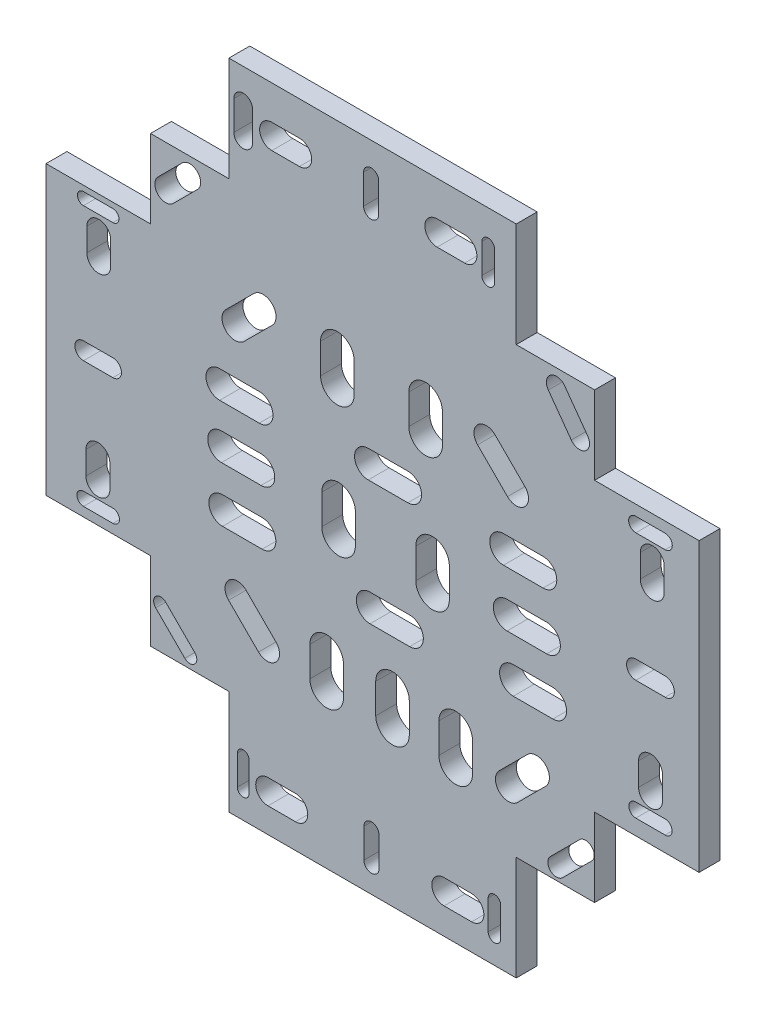
SolidWorks part; units mm, degrees
ref_plane "Front Plane" through (0, 0, 0) normal (0, 0, 1) x (1, 0, 0)
ref_plane "Top Plane" through (0, 0, 0) normal (0, 1, 0) x (1, 0, 0)
ref_plane "Right Plane" through (0, 0, 0) normal (1, 0, 0) x (0, 0, -1)
sketch "Sketch2" plane through (0, 0, 0) normal (0, 0, 1) x (1, 0, 0)
  line L0 (0, 0) -> (54.9967, 0)
  line L1 (54.9967, 0) -> (54.9967, 20.0012)
  line L2 (0, 0) -> (0, 20.0012)
  line L3 (0, 20.0012) -> (-15.0042, 20.0012)
  line L4 (-15.0042, 20.0012) -> (-15.0042, 34.9972)
  line L5 (-15.0042, 34.9972) -> (-35.003, 34.9972)
  line L6 (-35.003, 34.9972) -> (-35.003, 89.9966)
  line L7 (-35.003, 89.9966) -> (-15.0042, 89.9966)
  line L8 (-15.0042, 89.9966) -> (-15.0042, 104.9933)
  line L9 (-15.0042, 104.9933) -> (0, 104.9933)
  line L10 (0, 104.9933) -> (0, 124.9917)
  line L11 (0, 124.9917) -> (54.9967, 124.9917)
  line L12 (54.9967, 124.9917) -> (54.9967, 104.9933)
  line L13 (54.9967, 104.9933) -> (69.9972, 104.9933)
  line L14 (69.9972, 104.9933) -> (69.9972, 89.9966)
  line L15 (69.9972, 89.9966) -> (89.9963, 89.9966)
  line L16 (89.9963, 89.9966) -> (89.9963, 34.9972)
  line L17 (89.9963, 34.9972) -> (69.9972, 34.9972)
  line L18 (69.9972, 34.9972) -> (69.9972, 20.0012)
  line L19 (69.9972, 20.0012) -> (54.9967, 20.0012)
  line L20 (-27.8347, 38.0198) -> (-22.2091, 38.0198) construction
  line L21 (-27.8347, 39.2807) -> (-22.2091, 39.2807)
  line L22 (-27.8347, 36.7588) -> (-22.2091, 36.7588)
  line L23 (-27.8347, 87.778) -> (-22.2091, 87.778) construction
  line L24 (-27.8347, 88.9419) -> (-22.2091, 88.9419)
  line L25 (-27.8347, 86.6141) -> (-22.2091, 86.6141)
  line L26 (-27.8347, 62.5594) -> (-22.2091, 62.5594) construction
  line L27 (-27.8347, 64.2083) -> (-22.2091, 64.2083)
  line L28 (-27.8347, 60.9105) -> (-22.2091, 60.9105)
  line L29 (77.8808, 62.5594) -> (83.4988, 62.5594) construction
  line L30 (77.8808, 64.3223) -> (83.4988, 64.3223)
  line L31 (77.8808, 60.7965) -> (83.4988, 60.7965)
  line L32 (77.8808, 39.2807) -> (83.4988, 39.2807) construction
  line L33 (77.8808, 40.6133) -> (83.4988, 40.6133)
  line L34 (77.8808, 37.9481) -> (83.4988, 37.9481)
  line L35 (77.8808, 86.6141) -> (83.4988, 86.6141) construction
  line L36 (77.8808, 87.9828) -> (83.4988, 87.9828)
  line L37 (77.8808, 85.2454) -> (83.4988, 85.2454)
  line L38 (27.292, 4.9628) -> (27.292, 10.5841) construction
  line L39 (25.8409, 4.9628) -> (25.8409, 10.5841)
  line L40 (28.7431, 4.9628) -> (28.7431, 10.5841)
  line L41 (2.7367, 4.9628) -> (2.7367, 10.5841) construction
  line L42 (1.6165, 4.9628) -> (1.6165, 10.5841)
  line L43 (3.857, 4.9628) -> (3.857, 10.5841)
  line L44 (50.8285, 4.9628) -> (50.8285, 10.5841) construction
  line L45 (49.6282, 4.9628) -> (49.6282, 10.5841)
  line L46 (52.0288, 4.9628) -> (52.0288, 10.5841)
  line L47 (27.2281, 113.3425) -> (27.2281, 118.9638) construction
  line L50 (49.6282, 113.1494) -> (49.6282, 118.7625) construction
  line L51 (48.4049, 113.1494) -> (48.4049, 118.7625)
  line L52 (50.8515, 113.1494) -> (50.8515, 118.7625)
  line L53 (2.7367, 113.1494) -> (2.7367, 118.7625) construction
  line L54 (0.9482, 113.1494) -> (0.9482, 118.7625)
  line L55 (4.5253, 113.1494) -> (4.5253, 118.7625)
  line L56 (-13.0567, 27.8034) -> (-7.4882, 22.2349) construction
  line L57 (-12.1042, 28.7559) -> (-6.5356, 23.1874)
  line L58 (-14.0092, 26.8509) -> (-8.4407, 21.2823)
  line L59 (62.7052, 22.2349) -> (68.2737, 27.8034) construction
  line L60 (61.5328, 23.4072) -> (67.1014, 28.9758)
  line L61 (63.8775, 21.0625) -> (69.4461, 26.6311)
  line L62 (-12.1042, 97.0442) -> (-7.4882, 101.6603) construction
  line L63 (-13.5693, 98.5093) -> (-8.9533, 103.1254)
  line L64 (-10.6391, 95.5791) -> (-6.023, 100.1952)
  line L65 (62.7052, 101.6603) -> (67.1014, 95.5791) construction
  line L66 (64.2684, 102.7904) -> (68.6647, 96.7092)
  line L67 (61.1419, 100.5302) -> (65.5381, 94.449)
  line L68 (1.6165, 36.7588) -> (7.3377, 31.0376) construction
  line L69 (3.2847, 38.4271) -> (9.0059, 32.7059)
  line L70 (-0.0517, 35.0906) -> (5.6695, 29.3694)
  line L71 (58.873, 36.3537) -> (53.5044, 30.9851) construction
  line L72 (60.6273, 34.5995) -> (55.2587, 29.2309)
  line L73 (57.1187, 38.108) -> (51.7502, 32.7394)
  line L74 (6.5376, 86.6118) -> (1.169, 81.2432) construction
  line L75 (8.2918, 84.8575) -> (2.9233, 79.4889)
  line L76 (4.7833, 88.366) -> (-0.5853, 82.9975)
  line L77 (49.2661, 86.3508) -> (54.9873, 80.6296) construction
  line L78 (50.9344, 88.0191) -> (56.6556, 82.2979)
  line L79 (47.5979, 84.6826) -> (53.3191, 78.9614)
  line L80 (37.652, 81.1405) -> (37.652, 86.8617) construction
  line L81 (34.439, 81.1405) -> (34.439, 86.8617)
  line L82 (40.865, 81.1405) -> (40.865, 86.8617)
  line L83 (31.3153, 30.0156) -> (31.3153, 35.7368) construction
  line L84 (28.1023, 30.0156) -> (28.1023, 35.7368)
  line L85 (34.5283, 30.0156) -> (34.5283, 35.7368)
  line L86 (-1.2121, 49.3864) -> (6.3653, 49.3864) construction
  line L87 (-1.2121, 52.0097) -> (6.3653, 52.0097)
  line L88 (-1.2121, 46.7631) -> (6.3653, 46.7631)
  line L89 (-1.7652, 70.0017) -> (5.8123, 70.0017) construction
  line L90 (-1.7652, 72.625) -> (5.8123, 72.625)
  line L91 (-1.7652, 67.3784) -> (5.8123, 67.3784)
  line L92 (54.4341, 49.0547) -> (62.0115, 49.0547) construction
  line L93 (54.4341, 51.678) -> (62.0115, 51.678)
  line L94 (54.4341, 46.4314) -> (62.0115, 46.4314)
  line L95 (52.5607, 69.8314) -> (60.1382, 69.8314) construction
  line L96 (52.5607, 72.4547) -> (60.1382, 72.4547)
  line L97 (52.5607, 67.2081) -> (60.1382, 67.2081)
  line L98 (20.7566, 81.1058) -> (20.7566, 86.8269) construction
  line L99 (17.5436, 81.1058) -> (17.5436, 86.8269)
  line L100 (23.9696, 81.1058) -> (23.9696, 86.8269)
  line L101 (-1.4246, 59.8524) -> (6.1529, 59.8524) construction
  line L102 (-1.4246, 62.4757) -> (6.1529, 62.4757)
  line L103 (-1.4246, 57.2292) -> (6.1529, 57.2292)
  line L104 (53.2419, 59.2728) -> (60.8194, 59.2728) construction
  line L105 (53.2419, 61.896) -> (60.8194, 61.896)
  line L106 (53.2419, 56.6495) -> (60.8194, 56.6495)
  line L107 (18.713, 29.8453) -> (18.713, 35.5665) construction
  line L108 (15.5, 29.8453) -> (15.5, 35.5665)
  line L109 (21.926, 29.8453) -> (21.926, 35.5665)
  line L110 (43.4066, 29.5047) -> (43.4066, 35.2259) construction
  line L111 (40.1936, 29.5047) -> (40.1936, 35.2259)
  line L112 (46.6196, 29.5047) -> (46.6196, 35.2259)
  line L113 (20.9936, 56.2141) -> (20.9936, 61.9353) construction
  line L114 (17.7806, 56.2141) -> (17.7806, 61.9353)
  line L115 (24.2066, 56.2141) -> (24.2066, 61.9353)
  line L116 (38.9788, 56.2419) -> (38.9788, 61.9631) construction
  line L117 (35.7658, 56.2419) -> (35.7658, 61.9631)
  line L118 (42.1918, 56.2419) -> (42.1918, 61.9631)
  line L119 (27.0157, 47.3517) -> (34.5931, 47.3517) construction
  line L120 (27.0157, 49.975) -> (34.5931, 49.975)
  line L121 (27.0157, 44.7284) -> (34.5931, 44.7284)
  line L122 (26.6751, 71.0235) -> (34.2525, 71.0235) construction
  line L123 (26.6751, 73.6468) -> (34.2525, 73.6468)
  line L124 (26.6751, 68.4002) -> (34.2525, 68.4002)
  line L125 (25.777, 113.3425) -> (25.777, 118.9638)
  line L126 (28.6792, 113.3425) -> (28.6792, 118.9638)
  arc A0 (-27.8347, 39.2807) -> (-27.8347, 36.7588) centre (-27.8347, 38.0198) ccw
  arc A1 (-22.2091, 36.7588) -> (-22.2091, 39.2807) centre (-22.2091, 38.0198) ccw
  arc A2 (-27.8347, 88.9419) -> (-27.8347, 86.6141) centre (-27.8347, 87.778) ccw
  arc A3 (-22.2091, 86.6141) -> (-22.2091, 88.9419) centre (-22.2091, 87.778) ccw
  arc A4 (-27.8347, 64.2083) -> (-27.8347, 60.9105) centre (-27.8347, 62.5594) ccw
  arc A5 (-22.2091, 60.9105) -> (-22.2091, 64.2083) centre (-22.2091, 62.5594) ccw
  arc A6 (77.8808, 64.3223) -> (77.8808, 60.7965) centre (77.8808, 62.5594) ccw
  arc A7 (83.4988, 60.7965) -> (83.4988, 64.3223) centre (83.4988, 62.5594) ccw
  arc A8 (77.8808, 40.6133) -> (77.8808, 37.9481) centre (77.8808, 39.2807) ccw
  arc A9 (83.4988, 37.9481) -> (83.4988, 40.6133) centre (83.4988, 39.2807) ccw
  arc A10 (77.8808, 87.9828) -> (77.8808, 85.2454) centre (77.8808, 86.6141) ccw
  arc A11 (83.4988, 85.2454) -> (83.4988, 87.9828) centre (83.4988, 86.6141) ccw
  arc A12 (25.8409, 4.9628) -> (28.7431, 4.9628) centre (27.292, 4.9628) ccw
  arc A13 (28.7431, 10.5841) -> (25.8409, 10.5841) centre (27.292, 10.5841) ccw
  arc A14 (1.6165, 4.9628) -> (3.857, 4.9628) centre (2.7367, 4.9628) ccw
  arc A15 (3.857, 10.5841) -> (1.6165, 10.5841) centre (2.7367, 10.5841) ccw
  arc A16 (49.6282, 4.9628) -> (52.0288, 4.9628) centre (50.8285, 4.9628) ccw
  arc A17 (52.0288, 10.5841) -> (49.6282, 10.5841) centre (50.8285, 10.5841) ccw
  arc A20 (48.4049, 113.1494) -> (50.8515, 113.1494) centre (49.6282, 113.1494) ccw
  arc A21 (50.8515, 118.7625) -> (48.4049, 118.7625) centre (49.6282, 118.7625) ccw
  arc A22 (0.9482, 113.1494) -> (4.5253, 113.1494) centre (2.7367, 113.1494) ccw
  arc A23 (4.5253, 118.7625) -> (0.9482, 118.7625) centre (2.7367, 118.7625) ccw
  arc A24 (-12.1042, 28.7559) -> (-14.0092, 26.8509) centre (-13.0567, 27.8034) ccw
  arc A25 (-8.4407, 21.2823) -> (-6.5356, 23.1874) centre (-7.4882, 22.2349) ccw
  arc A26 (61.5328, 23.4072) -> (63.8775, 21.0625) centre (62.7052, 22.2349) ccw
  arc A27 (69.4461, 26.6311) -> (67.1014, 28.9758) centre (68.2737, 27.8034) ccw
  arc A28 (-13.5693, 98.5093) -> (-10.6391, 95.5791) centre (-12.1042, 97.0442) ccw
  arc A29 (-6.023, 100.1952) -> (-8.9533, 103.1254) centre (-7.4882, 101.6603) ccw
  arc A30 (64.2684, 102.7904) -> (61.1419, 100.5302) centre (62.7052, 101.6603) ccw
  arc A31 (65.5381, 94.449) -> (68.6647, 96.7092) centre (67.1014, 95.5791) ccw
  arc A32 (3.2847, 38.4271) -> (-0.0517, 35.0906) centre (1.6165, 36.7588) ccw
  arc A33 (5.6695, 29.3694) -> (9.0059, 32.7059) centre (7.3377, 31.0376) ccw
  arc A34 (60.6273, 34.5995) -> (57.1187, 38.108) centre (58.873, 36.3537) ccw
  arc A35 (51.7502, 32.7394) -> (55.2587, 29.2309) centre (53.5044, 30.9851) ccw
  arc A36 (8.2918, 84.8575) -> (4.7833, 88.366) centre (6.5376, 86.6118) ccw
  arc A37 (-0.5853, 82.9975) -> (2.9233, 79.4889) centre (1.169, 81.2432) ccw
  arc A38 (50.9344, 88.0191) -> (47.5979, 84.6826) centre (49.2661, 86.3508) ccw
  arc A39 (53.3191, 78.9614) -> (56.6556, 82.2979) centre (54.9873, 80.6296) ccw
  arc A40 (34.439, 81.1405) -> (40.865, 81.1405) centre (37.652, 81.1405) ccw
  arc A41 (40.865, 86.8617) -> (34.439, 86.8617) centre (37.652, 86.8617) ccw
  arc A42 (28.1023, 30.0156) -> (34.5283, 30.0156) centre (31.3153, 30.0156) ccw
  arc A43 (34.5283, 35.7368) -> (28.1023, 35.7368) centre (31.3153, 35.7368) ccw
  arc A44 (-1.2121, 52.0097) -> (-1.2121, 46.7631) centre (-1.2121, 49.3864) ccw
  arc A45 (6.3653, 46.7631) -> (6.3653, 52.0097) centre (6.3653, 49.3864) ccw
  arc A46 (-1.7652, 72.625) -> (-1.7652, 67.3784) centre (-1.7652, 70.0017) ccw
  arc A47 (5.8123, 67.3784) -> (5.8123, 72.625) centre (5.8123, 70.0017) ccw
  arc A48 (54.4341, 51.678) -> (54.4341, 46.4314) centre (54.4341, 49.0547) ccw
  arc A49 (62.0115, 46.4314) -> (62.0115, 51.678) centre (62.0115, 49.0547) ccw
  arc A50 (52.5607, 72.4547) -> (52.5607, 67.2081) centre (52.5607, 69.8314) ccw
  arc A51 (60.1382, 67.2081) -> (60.1382, 72.4547) centre (60.1382, 69.8314) ccw
  arc A52 (17.5436, 81.1058) -> (23.9696, 81.1058) centre (20.7566, 81.1058) ccw
  arc A53 (23.9696, 86.8269) -> (17.5436, 86.8269) centre (20.7566, 86.8269) ccw
  arc A54 (-1.4246, 62.4757) -> (-1.4246, 57.2292) centre (-1.4246, 59.8524) ccw
  arc A55 (6.1529, 57.2292) -> (6.1529, 62.4757) centre (6.1529, 59.8524) ccw
  arc A56 (53.2419, 61.896) -> (53.2419, 56.6495) centre (53.2419, 59.2728) ccw
  arc A57 (60.8194, 56.6495) -> (60.8194, 61.896) centre (60.8194, 59.2728) ccw
  arc A58 (15.5, 29.8453) -> (21.926, 29.8453) centre (18.713, 29.8453) ccw
  arc A59 (21.926, 35.5665) -> (15.5, 35.5665) centre (18.713, 35.5665) ccw
  arc A60 (40.1936, 29.5047) -> (46.6196, 29.5047) centre (43.4066, 29.5047) ccw
  arc A61 (46.6196, 35.2259) -> (40.1936, 35.2259) centre (43.4066, 35.2259) ccw
  arc A62 (17.7806, 56.2141) -> (24.2066, 56.2141) centre (20.9936, 56.2141) ccw
  arc A63 (24.2066, 61.9353) -> (17.7806, 61.9353) centre (20.9936, 61.9353) ccw
  arc A64 (35.7658, 56.2419) -> (42.1918, 56.2419) centre (38.9788, 56.2419) ccw
  arc A65 (42.1918, 61.9631) -> (35.7658, 61.9631) centre (38.9788, 61.9631) ccw
  arc A66 (27.0157, 49.975) -> (27.0157, 44.7284) centre (27.0157, 47.3517) ccw
  arc A67 (34.5931, 44.7284) -> (34.5931, 49.975) centre (34.5931, 47.3517) ccw
  arc A68 (26.6751, 73.6468) -> (26.6751, 68.4002) centre (26.6751, 71.0235) ccw
  arc A69 (34.2525, 68.4002) -> (34.2525, 73.6468) centre (34.2525, 71.0235) ccw
  arc A70 (25.777, 113.3425) -> (28.6792, 113.3425) centre (27.2281, 113.3425) ccw
  arc A71 (28.6792, 118.9638) -> (25.777, 118.9638) centre (27.2281, 118.9638) ccw
  point P23 (-25.0219, 38.0198)
  point P30 (-25.0219, 87.778)
  point P35 (-25.0219, 62.5594)
  point P42 (-25.0219, 60.9105)
  point P45 (80.6898, 62.5594)
  point P50 (80.6898, 39.2807)
  point P57 (80.6898, 86.6141)
  point P64 (27.292, 7.7735)
  point P71 (2.7367, 7.7735)
  point P78 (50.8285, 7.7735)
  point P85 (27.2281, 116.1532)
  point P92 (49.6282, 115.9559)
  point P99 (2.7367, 115.9559)
  point P108 (-10.2724, 25.0191)
  point P113 (65.4895, 25.0191)
  point P120 (-9.7962, 99.3523)
  point P127 (64.9033, 98.6197)
  point P136 (4.4771, 33.8982)
  point P143 (56.1887, 33.6694)
  point P150 (3.8533, 83.9275)
  point P157 (52.1267, 83.4902)
  point P162 (37.652, 84.0011)
  point P176 (31.3153, 32.8762)
  point P188 (2.5766, 49.3864)
  point P196 (2.0236, 70.0017)
  point P203 (58.2228, 49.0547)
  point P210 (56.3495, 69.8314)
  point P216 (20.7566, 83.9664)
  point P225 (2.3642, 59.8524)
  point P232 (57.0307, 59.2728)
  point P237 (18.713, 32.7059)
  point P244 (43.4066, 32.3653)
  point P251 (20.9936, 59.0747)
  point P258 (38.9788, 59.1025)
  point P267 (30.8044, 47.3517)
  point P274 (30.4638, 71.0235)
  dimension "D1" = 2.8128
sketch "Sketch3" plane through (0, 0, 0) normal (0, 0, 1) x (1, 0, 0)
  line L0 (0, 0) -> (54.9967, 0)
  line L1 (54.9967, 0) -> (54.9967, 20.0012)
  line L2 (0, 0) -> (0, 20.0012)
  line L3 (0, 20.0012) -> (-15.0042, 20.0012)
  line L4 (-15.0042, 20.0012) -> (-15.0042, 34.9972)
  line L5 (-15.0042, 34.9972) -> (-35.003, 34.9972)
  line L6 (-35.003, 34.9972) -> (-35.003, 89.9966)
  line L7 (-35.003, 89.9966) -> (-15.0042, 89.9966)
  line L8 (-15.0042, 89.9966) -> (-15.0042, 104.9933)
  line L9 (-15.0042, 104.9933) -> (0, 104.9933)
  line L10 (0, 104.9933) -> (0, 124.9917)
  line L11 (0, 124.9917) -> (54.9967, 124.9917)
  line L12 (54.9967, 124.9917) -> (54.9967, 104.9933)
  line L13 (54.9967, 104.9933) -> (69.9972, 104.9933)
  line L14 (69.9972, 104.9933) -> (69.9972, 89.9966)
  line L15 (69.9972, 89.9966) -> (89.9963, 89.9966)
  line L16 (89.9963, 89.9966) -> (89.9963, 34.9972)
  line L17 (89.9963, 34.9972) -> (69.9972, 34.9972)
  line L18 (69.9972, 34.9972) -> (69.9972, 20.0012)
  line L19 (69.9972, 20.0012) -> (54.9967, 20.0012)
extrude "Boss-Extrude1" add sketch "Sketch3" along normal blind 4
sketch "Sketch4" plane through (-9.7962, 99.3523, 0) normal (0, 0, 1) x (1, 0, 0)
  line L0 (8.031, -26.7273) -> (15.6085, -26.7273)
  line L1 (-18.0386, -61.3325) -> (-12.4129, -61.3325) construction
  line L2 (-18.0386, -60.0716) -> (-12.4129, -60.0716)
  line L3 (-18.0386, -62.5934) -> (-12.4129, -62.5934)
  line L4 (-18.0386, -11.5743) -> (-12.4129, -11.5743) construction
  line L5 (-18.0386, -10.4103) -> (-12.4129, -10.4103)
  line L6 (-18.0386, -12.7382) -> (-12.4129, -12.7382)
  line L7 (-18.0386, -36.7929) -> (-12.4129, -36.7929) construction
  line L8 (-18.0386, -35.1439) -> (-12.4129, -35.1439)
  line L9 (-18.0386, -38.4418) -> (-12.4129, -38.4418)
  line L10 (87.677, -36.7929) -> (93.295, -36.7929) construction
  line L11 (87.677, -35.03) -> (93.295, -35.03)
  line L12 (87.677, -38.5557) -> (93.295, -38.5557)
  line L13 (87.677, -60.0716) -> (93.295, -60.0716) construction
  line L14 (87.677, -58.739) -> (93.295, -58.739)
  line L15 (87.677, -61.4041) -> (93.295, -61.4041)
  line L16 (87.677, -12.7382) -> (93.295, -12.7382) construction
  line L17 (87.677, -11.3695) -> (93.295, -11.3695)
  line L18 (87.677, -14.1069) -> (93.295, -14.1069)
  line L19 (37.0882, -94.3894) -> (37.0882, -88.7681) construction
  line L20 (35.6371, -94.3894) -> (35.6371, -88.7681)
  line L21 (38.5393, -94.3894) -> (38.5393, -88.7681)
  line L22 (12.5329, -94.3894) -> (12.5329, -88.7681) construction
  line L23 (11.4127, -94.3894) -> (11.4127, -88.7681)
  line L24 (13.6532, -94.3894) -> (13.6532, -88.7681)
  line L25 (60.6246, -94.3894) -> (60.6246, -88.7681) construction
  line L26 (59.4244, -94.3894) -> (59.4244, -88.7681)
  line L27 (61.8249, -94.3894) -> (61.8249, -88.7681)
  line L28 (59.4244, 13.7971) -> (59.4244, 19.4103) construction
  line L29 (58.2011, 13.7971) -> (58.2011, 19.4103)
  line L30 (60.6476, 13.7971) -> (60.6476, 19.4103)
  line L31 (12.5329, 13.7971) -> (12.5329, 19.4103) construction
  line L32 (10.7444, 13.7971) -> (10.7444, 19.4103)
  line L33 (14.3215, 13.7971) -> (14.3215, 19.4103)
  line L34 (-3.2605, -71.5488) -> (2.308, -77.1174) construction
  line L35 (-2.308, -70.5963) -> (3.2605, -76.1649)
  line L36 (-4.2131, -72.5013) -> (1.3555, -78.0699)
  line L37 (72.5013, -77.1174) -> (78.0699, -71.5488) construction
  line L38 (71.329, -75.9451) -> (76.8976, -70.3765)
  line L39 (73.6737, -78.2897) -> (79.2423, -72.7212)
  line L40 (-2.308, -2.308) -> (2.308, 2.308) construction
  line L41 (-3.7731, -0.8429) -> (0.8429, 3.7731)
  line L42 (-0.8429, -3.7731) -> (3.7731, 0.8429)
  line L43 (72.5013, 2.308) -> (76.8976, -3.7731) construction
  line L44 (74.0646, 3.4382) -> (78.4609, -2.643)
  line L45 (70.9381, 1.1779) -> (75.3343, -4.9033)
  line L46 (11.4127, -62.5934) -> (17.1339, -68.3146) construction
  line L47 (13.0809, -60.9252) -> (18.8021, -66.6464)
  line L48 (9.7444, -64.2616) -> (15.4656, -69.9828)
  line L49 (68.6692, -62.9985) -> (63.3006, -68.3671) construction
  line L50 (70.4234, -64.7528) -> (65.0549, -70.1214)
  line L51 (66.9149, -61.2443) -> (61.5463, -66.6128)
  line L52 (16.3338, -12.7405) -> (10.9652, -18.1091) construction
  line L53 (18.088, -14.4948) -> (12.7195, -19.8633)
  line L54 (14.5795, -10.9862) -> (9.2109, -16.3548)
  line L55 (59.0623, -13.0014) -> (64.7835, -18.7226) construction
  line L56 (60.7305, -11.3332) -> (66.4517, -17.0544)
  line L57 (57.3941, -14.6696) -> (63.1153, -20.3908)
  line L58 (47.4482, -18.2117) -> (47.4482, -12.4905) construction
  line L59 (44.2352, -18.2117) -> (44.2352, -12.4905)
  line L60 (50.6612, -18.2117) -> (50.6612, -12.4905)
  line L61 (41.1115, -69.3367) -> (41.1115, -63.6155) construction
  line L62 (37.8985, -69.3367) -> (37.8985, -63.6155)
  line L63 (44.3244, -69.3367) -> (44.3244, -63.6155)
  line L64 (8.584, -49.9659) -> (16.1615, -49.9659) construction
  line L65 (8.584, -47.3426) -> (16.1615, -47.3426)
  line L66 (8.584, -52.5891) -> (16.1615, -52.5891)
  line L67 (8.031, -29.3506) -> (15.6085, -29.3506) construction
  line L68 (8.031, -31.9738) -> (15.6085, -31.9738)
  line L69 (64.2302, -50.2975) -> (71.8077, -50.2975) construction
  line L70 (64.2302, -47.6743) -> (71.8077, -47.6743)
  line L71 (64.2302, -52.9208) -> (71.8077, -52.9208)
  line L72 (62.3569, -29.5209) -> (69.9344, -29.5209) construction
  line L73 (62.3569, -26.8976) -> (69.9344, -26.8976)
  line L74 (62.3569, -32.1441) -> (69.9344, -32.1441)
  line L75 (30.5528, -18.2465) -> (30.5528, -12.5253) construction
  line L76 (27.3398, -18.2465) -> (27.3398, -12.5253)
  line L77 (33.7658, -18.2465) -> (33.7658, -12.5253)
  line L78 (8.3716, -39.4998) -> (15.9491, -39.4998) construction
  line L79 (8.3716, -36.8766) -> (15.9491, -36.8766)
  line L80 (8.3716, -42.1231) -> (15.9491, -42.1231)
  line L81 (63.0381, -40.0795) -> (70.6156, -40.0795) construction
  line L82 (63.0381, -37.4562) -> (70.6156, -37.4562)
  line L83 (63.0381, -42.7028) -> (70.6156, -42.7028)
  line L84 (28.5092, -69.507) -> (28.5092, -63.7858) construction
  line L85 (25.2962, -69.507) -> (25.2962, -63.7858)
  line L86 (31.7222, -69.507) -> (31.7222, -63.7858)
  line L87 (53.2028, -69.8476) -> (53.2028, -64.1264) construction
  line L88 (49.9898, -69.8476) -> (49.9898, -64.1264)
  line L89 (56.4158, -69.8476) -> (56.4158, -64.1264)
  line L90 (30.7898, -43.1382) -> (30.7898, -37.417) construction
  line L91 (27.5768, -43.1382) -> (27.5768, -37.417)
  line L92 (34.0027, -43.1382) -> (34.0027, -37.417)
  line L93 (48.775, -43.1104) -> (48.775, -37.3892) construction
  line L94 (45.562, -43.1104) -> (45.562, -37.3892)
  line L95 (51.988, -43.1104) -> (51.988, -37.3892)
  line L96 (36.8118, -52.0005) -> (44.3893, -52.0005) construction
  line L97 (36.8118, -49.3773) -> (44.3893, -49.3773)
  line L98 (36.8118, -54.6238) -> (44.3893, -54.6238)
  line L99 (36.4712, -28.3288) -> (44.0487, -28.3288) construction
  line L100 (36.4712, -25.7055) -> (44.0487, -25.7055)
  line L101 (36.4712, -30.952) -> (44.0487, -30.952)
  arc A0 (-18.0386, -60.0716) -> (-18.0386, -62.5934) centre (-18.0386, -61.3325) ccw
  arc A1 (-12.4129, -62.5934) -> (-12.4129, -60.0716) centre (-12.4129, -61.3325) ccw
  arc A2 (-18.0386, -10.4103) -> (-18.0386, -12.7382) centre (-18.0386, -11.5743) ccw
  arc A3 (-12.4129, -12.7382) -> (-12.4129, -10.4103) centre (-12.4129, -11.5743) ccw
  arc A4 (-18.0386, -35.1439) -> (-18.0386, -38.4418) centre (-18.0386, -36.7929) ccw
  arc A5 (-12.4129, -38.4418) -> (-12.4129, -35.1439) centre (-12.4129, -36.7929) ccw
  arc A6 (87.677, -35.03) -> (87.677, -38.5557) centre (87.677, -36.7929) ccw
  arc A7 (93.295, -38.5557) -> (93.295, -35.03) centre (93.295, -36.7929) ccw
  arc A8 (87.677, -58.739) -> (87.677, -61.4041) centre (87.677, -60.0716) ccw
  arc A9 (93.295, -61.4041) -> (93.295, -58.739) centre (93.295, -60.0716) ccw
  arc A10 (87.677, -11.3695) -> (87.677, -14.1069) centre (87.677, -12.7382) ccw
  arc A11 (93.295, -14.1069) -> (93.295, -11.3695) centre (93.295, -12.7382) ccw
  arc A12 (35.6371, -94.3894) -> (38.5393, -94.3894) centre (37.0882, -94.3894) ccw
  arc A13 (38.5393, -88.7681) -> (35.6371, -88.7681) centre (37.0882, -88.7681) ccw
  arc A14 (11.4127, -94.3894) -> (13.6532, -94.3894) centre (12.5329, -94.3894) ccw
  arc A15 (13.6532, -88.7681) -> (11.4127, -88.7681) centre (12.5329, -88.7681) ccw
  arc A16 (59.4244, -94.3894) -> (61.8249, -94.3894) centre (60.6246, -94.3894) ccw
  arc A17 (61.8249, -88.7681) -> (59.4244, -88.7681) centre (60.6246, -88.7681) ccw
  arc A18 (58.2011, 13.7971) -> (60.6476, 13.7971) centre (59.4244, 13.7971) ccw
  arc A19 (60.6476, 19.4103) -> (58.2011, 19.4103) centre (59.4244, 19.4103) ccw
  arc A20 (10.7444, 13.7971) -> (14.3215, 13.7971) centre (12.5329, 13.7971) ccw
  arc A21 (14.3215, 19.4103) -> (10.7444, 19.4103) centre (12.5329, 19.4103) ccw
  arc A22 (-2.308, -70.5963) -> (-4.2131, -72.5013) centre (-3.2605, -71.5488) ccw
  arc A23 (1.3555, -78.0699) -> (3.2605, -76.1649) centre (2.308, -77.1174) ccw
  arc A24 (71.329, -75.9451) -> (73.6737, -78.2897) centre (72.5013, -77.1174) ccw
  arc A25 (79.2423, -72.7212) -> (76.8976, -70.3765) centre (78.0699, -71.5488) ccw
  arc A26 (-3.7731, -0.8429) -> (-0.8429, -3.7731) centre (-2.308, -2.308) ccw
  arc A27 (3.7731, 0.8429) -> (0.8429, 3.7731) centre (2.308, 2.308) ccw
  arc A28 (74.0646, 3.4382) -> (70.9381, 1.1779) centre (72.5013, 2.308) ccw
  arc A29 (75.3343, -4.9033) -> (78.4609, -2.643) centre (76.8976, -3.7731) ccw
  arc A30 (13.0809, -60.9252) -> (9.7444, -64.2616) centre (11.4127, -62.5934) ccw
  arc A31 (15.4656, -69.9828) -> (18.8021, -66.6464) centre (17.1339, -68.3146) ccw
  arc A32 (70.4234, -64.7528) -> (66.9149, -61.2443) centre (68.6692, -62.9985) ccw
  arc A33 (61.5463, -66.6128) -> (65.0549, -70.1214) centre (63.3006, -68.3671) ccw
  arc A34 (18.088, -14.4948) -> (14.5795, -10.9862) centre (16.3338, -12.7405) ccw
  arc A35 (9.2109, -16.3548) -> (12.7195, -19.8633) centre (10.9652, -18.1091) ccw
  arc A36 (60.7305, -11.3332) -> (57.3941, -14.6696) centre (59.0623, -13.0014) ccw
  arc A37 (63.1153, -20.3908) -> (66.4517, -17.0544) centre (64.7835, -18.7226) ccw
  arc A38 (44.2352, -18.2117) -> (50.6612, -18.2117) centre (47.4482, -18.2117) ccw
  arc A39 (50.6612, -12.4905) -> (44.2352, -12.4905) centre (47.4482, -12.4905) ccw
  arc A40 (37.8985, -69.3367) -> (44.3244, -69.3367) centre (41.1115, -69.3367) ccw
  arc A41 (44.3244, -63.6155) -> (37.8985, -63.6155) centre (41.1115, -63.6155) ccw
  arc A42 (8.584, -47.3426) -> (8.584, -52.5891) centre (8.584, -49.9659) ccw
  arc A43 (16.1615, -52.5891) -> (16.1615, -47.3426) centre (16.1615, -49.9659) ccw
  arc A44 (8.031, -26.7273) -> (8.031, -31.9738) centre (8.031, -29.3506) ccw
  arc A45 (15.6085, -31.9738) -> (15.6085, -26.7273) centre (15.6085, -29.3506) ccw
  arc A46 (64.2302, -47.6743) -> (64.2302, -52.9208) centre (64.2302, -50.2975) ccw
  arc A47 (71.8077, -52.9208) -> (71.8077, -47.6743) centre (71.8077, -50.2975) ccw
  arc A48 (62.3569, -26.8976) -> (62.3569, -32.1441) centre (62.3569, -29.5209) ccw
  arc A49 (69.9344, -32.1441) -> (69.9344, -26.8976) centre (69.9344, -29.5209) ccw
  arc A50 (27.3398, -18.2465) -> (33.7658, -18.2465) centre (30.5528, -18.2465) ccw
  arc A51 (33.7658, -12.5253) -> (27.3398, -12.5253) centre (30.5528, -12.5253) ccw
  arc A52 (8.3716, -36.8766) -> (8.3716, -42.1231) centre (8.3716, -39.4998) ccw
  arc A53 (15.9491, -42.1231) -> (15.9491, -36.8766) centre (15.9491, -39.4998) ccw
  arc A54 (63.0381, -37.4562) -> (63.0381, -42.7028) centre (63.0381, -40.0795) ccw
  arc A55 (70.6156, -42.7028) -> (70.6156, -37.4562) centre (70.6156, -40.0795) ccw
  arc A56 (25.2962, -69.507) -> (31.7222, -69.507) centre (28.5092, -69.507) ccw
  arc A57 (31.7222, -63.7858) -> (25.2962, -63.7858) centre (28.5092, -63.7858) ccw
  arc A58 (49.9898, -69.8476) -> (56.4158, -69.8476) centre (53.2028, -69.8476) ccw
  arc A59 (56.4158, -64.1264) -> (49.9898, -64.1264) centre (53.2028, -64.1264) ccw
  arc A60 (27.5768, -43.1382) -> (34.0027, -43.1382) centre (30.7898, -43.1382) ccw
  arc A61 (34.0027, -37.417) -> (27.5768, -37.417) centre (30.7898, -37.417) ccw
  arc A62 (45.562, -43.1104) -> (51.988, -43.1104) centre (48.775, -43.1104) ccw
  arc A63 (51.988, -37.3892) -> (45.562, -37.3892) centre (48.775, -37.3892) ccw
  arc A64 (36.8118, -49.3773) -> (36.8118, -54.6238) centre (36.8118, -52.0005) ccw
  arc A65 (44.3893, -54.6238) -> (44.3893, -49.3773) centre (44.3893, -52.0005) ccw
  arc A66 (36.4712, -25.7055) -> (36.4712, -30.952) centre (36.4712, -28.3288) ccw
  arc A67 (44.0487, -30.952) -> (44.0487, -25.7055) centre (44.0487, -28.3288) ccw
  point P2 (-15.2257, -61.3325)
  point P9 (-15.2257, -11.5743)
  point P14 (-15.2257, -36.7929)
  point P24 (90.486, -36.7929)
  point P29 (90.486, -60.0716)
  point P36 (90.486, -12.7382)
  point P43 (37.0882, -91.5788)
  point P50 (12.5329, -91.5788)
  point P57 (60.6246, -91.5788)
  point P64 (59.4244, 16.6037)
  point P71 (12.5329, 16.6037)
  point P80 (-0.4763, -74.3331)
  point P85 (75.2856, -74.3331)
  point P92 (0, 0)
  point P99 (74.6995, -0.7326)
  point P108 (14.2733, -65.454)
  point P115 (65.9849, -65.6828)
  point P122 (13.6495, -15.4248)
  point P129 (61.9229, -15.862)
  point P134 (47.4482, -15.3511)
  point P141 (41.1115, -66.4761)
  point P150 (12.3728, -49.9659)
  point P157 (11.8197, -29.3506)
  point P164 (68.019, -50.2975)
  point P171 (66.1456, -29.5209)
  point P176 (30.5528, -15.3859)
  point P185 (12.1603, -39.4998)
  point P192 (66.8268, -40.0795)
  point P197 (28.5092, -66.6464)
  point P204 (53.2028, -66.987)
  point P211 (30.7898, -40.2776)
  point P218 (48.775, -40.2498)
  point P227 (40.6006, -52.0005)
  point P234 (40.26, -28.3288)
extrude "Cut-Extrude1" cut sketch "Sketch4" against normal blind 4 and the other way blind 34
sketch "Sketch5" plane through (27.2281, 116.1532, 0) normal (0, 0, 1) x (1, 0, 0)
  line L0 (0, -2.8106) -> (0, 2.8106) construction
  line L1 (-1.4511, -2.8106) -> (-1.4511, 2.8106)
  line L2 (1.4511, -2.8106) -> (1.4511, 2.8106)
  arc A0 (-1.4511, -2.8106) -> (1.4511, -2.8106) centre (0, -2.8106) ccw
  arc A1 (1.4511, 2.8106) -> (-1.4511, 2.8106) centre (0, 2.8106) ccw
  point P0 (0, 0)
extrude "Cut-Extrude2" cut sketch "Sketch5" against normal blind 4 and the other way blind 24
sketch "Sketch6" plane through (0, 0, 0) normal (0, 0, 1) x (1, 0, 0)
  line L53 (2.7367, 113.1494) -> (2.7367, 118.7625) construction
  line L54 (0.9482, 113.1494) -> (0.9482, 118.7625)
  line L55 (4.5253, 113.1494) -> (4.5253, 118.7625)
  arc A22 (0.9482, 113.1494) -> (4.5253, 113.1494) centre (2.7367, 113.1494) ccw
  arc A23 (4.5253, 118.7625) -> (0.9482, 118.7625) centre (2.7367, 118.7625) ccw
  point P99 (2.7367, 115.9559)
sketch "Sketch7" plane through (0, 0, 4) normal (0, 0, 1) x (1, 0, 0)
  line L0 (8.2237, 116.1115) -> (13.498, 116.1115) construction
  line L1 (8.2237, 118.4556) -> (13.498, 118.4556)
  line L2 (8.2237, 113.7674) -> (13.498, 113.7674)
  line L3 (39.8525, 115.9211) -> (45.1267, 115.9211) construction
  line L4 (39.8525, 118.2652) -> (45.1267, 118.2652)
  line L5 (39.8525, 113.577) -> (45.1267, 113.577)
  line L6 (7.4786, 7.125) -> (12.7528, 7.125) construction
  line L7 (7.4786, 9.4691) -> (12.7528, 9.4691)
  line L8 (7.4786, 4.7809) -> (12.7528, 4.7809)
  line L9 (41.1825, 7.3906) -> (46.4568, 7.3906) construction
  line L10 (41.1825, 9.7347) -> (46.4568, 9.7347)
  line L11 (41.1825, 5.0465) -> (46.4568, 5.0465)
  line L12 (-25.0775, 42.0455) -> (-25.0775, 46.4493) construction
  line L13 (-27.3675, 42.0455) -> (-27.3675, 46.4493)
  line L14 (-22.7875, 42.0455) -> (-22.7875, 46.4493)
  line L15 (-24.9073, 79.1232) -> (-24.9073, 83.527) construction
  line L16 (-27.1973, 79.1232) -> (-27.1973, 83.527)
  line L17 (-22.6173, 79.1232) -> (-22.6173, 83.527)
  line L18 (80.7042, 43.3219) -> (80.7042, 47.7257) construction
  line L19 (78.4142, 43.3219) -> (78.4142, 47.7257)
  line L20 (82.9942, 43.3219) -> (82.9942, 47.7257)
  line L21 (81.0386, 78.0156) -> (81.0386, 82.4194) construction
  line L22 (78.7486, 78.0156) -> (78.7486, 82.4194)
  line L23 (83.3286, 78.0156) -> (83.3286, 82.4194)
  arc A0 (8.2237, 118.4556) -> (8.2237, 113.7674) centre (8.2237, 116.1115) ccw
  arc A1 (13.498, 113.7674) -> (13.498, 118.4556) centre (13.498, 116.1115) ccw
  arc A2 (39.8525, 118.2652) -> (39.8525, 113.577) centre (39.8525, 115.9211) ccw
  arc A3 (45.1267, 113.577) -> (45.1267, 118.2652) centre (45.1267, 115.9211) ccw
  arc A4 (7.4786, 9.4691) -> (7.4786, 4.7809) centre (7.4786, 7.125) ccw
  arc A5 (12.7528, 4.7809) -> (12.7528, 9.4691) centre (12.7528, 7.125) ccw
  arc A6 (41.1825, 9.7347) -> (41.1825, 5.0465) centre (41.1825, 7.3906) ccw
  arc A7 (46.4568, 5.0465) -> (46.4568, 9.7347) centre (46.4568, 7.3906) ccw
  arc A8 (-27.3675, 42.0455) -> (-22.7875, 42.0455) centre (-25.0775, 42.0455) ccw
  arc A9 (-22.7875, 46.4493) -> (-27.3675, 46.4493) centre (-25.0775, 46.4493) ccw
  arc A10 (-27.1973, 79.1232) -> (-22.6173, 79.1232) centre (-24.9073, 79.1232) ccw
  arc A11 (-22.6173, 83.527) -> (-27.1973, 83.527) centre (-24.9073, 83.527) ccw
  arc A12 (78.4142, 43.3219) -> (82.9942, 43.3219) centre (80.7042, 43.3219) ccw
  arc A13 (82.9942, 47.7257) -> (78.4142, 47.7257) centre (80.7042, 47.7257) ccw
  arc A14 (78.7486, 78.0156) -> (83.3286, 78.0156) centre (81.0386, 78.0156) ccw
  arc A15 (83.3286, 82.4194) -> (78.7486, 82.4194) centre (81.0386, 82.4194) ccw
  point P2 (10.8609, 116.1115)
  point P9 (42.4896, 115.9211)
  point P14 (-25.0775, 44.2474)
  point P19 (10.1157, 7.125)
  point P26 (43.8196, 7.3906)
  point P35 (-24.9073, 81.3251)
  point P42 (80.7042, 45.5238)
  point P49 (81.0386, 80.2175)
  point P56 (0, 0)
  dimension "D1" = 37.0781
sketch "Sketch8" plane through (0, 0, 4) normal (0, 0, 1) x (1, 0, 0)
  line L0 (41.1825, 9.7347) -> (46.4568, 9.7347)
  line L1 (41.1825, 5.0465) -> (46.4568, 5.0465)
  line L2 (41.1825, 7.3906) -> (46.4568, 7.3906) construction
  arc A0 (41.1825, 9.7347) -> (41.1825, 5.0465) centre (41.1825, 7.3906) ccw
  arc A1 (46.4568, 5.0465) -> (46.4568, 9.7347) centre (46.4568, 7.3906) ccw
  point P2 (43.8196, 7.3906)
extrude "Cut-Extrude3" cut sketch "Sketch8" against normal blind 10
sketch "Sketch9" plane through (81.0386, 80.2175, 4) normal (0, 0, 1) x (1, 0, 0)
  line L0 (-72.8148, 35.8941) -> (-67.5406, 35.8941) construction
  line L1 (-72.8148, 38.2382) -> (-67.5406, 38.2382)
  line L2 (-72.8148, 33.55) -> (-67.5406, 33.55)
  line L3 (-41.1861, 35.7036) -> (-35.9119, 35.7036) construction
  line L4 (-41.1861, 38.0477) -> (-35.9119, 38.0477)
  line L5 (-41.1861, 33.3595) -> (-35.9119, 33.3595)
  line L6 (-73.56, -73.0925) -> (-68.2858, -73.0925) construction
  line L7 (-73.56, -70.7484) -> (-68.2858, -70.7484)
  line L8 (-73.56, -75.4366) -> (-68.2858, -75.4366)
  line L9 (-106.1161, -38.172) -> (-106.1161, -33.7682) construction
  line L10 (-108.406, -38.172) -> (-108.406, -33.7682)
  line L11 (-103.8261, -38.172) -> (-103.8261, -33.7682)
  line L12 (-105.9458, -1.0943) -> (-105.9458, 3.3096) construction
  line L13 (-108.2358, -1.0943) -> (-108.2358, 3.3096)
  line L14 (-103.6559, -1.0943) -> (-103.6559, 3.3096)
  line L15 (-0.3344, -36.8956) -> (-0.3344, -32.4917) construction
  line L16 (-2.6244, -36.8956) -> (-2.6244, -32.4917)
  line L17 (1.9556, -36.8956) -> (1.9556, -32.4917)
  line L18 (0, -2.2019) -> (0, 2.2019) construction
  line L19 (-2.29, -2.2019) -> (-2.29, 2.2019)
  line L20 (2.29, -2.2019) -> (2.29, 2.2019)
  arc A0 (-72.8148, 38.2382) -> (-72.8148, 33.55) centre (-72.8148, 35.8941) ccw
  arc A1 (-67.5406, 33.55) -> (-67.5406, 38.2382) centre (-67.5406, 35.8941) ccw
  arc A2 (-41.1861, 38.0477) -> (-41.1861, 33.3595) centre (-41.1861, 35.7036) ccw
  arc A3 (-35.9119, 33.3595) -> (-35.9119, 38.0477) centre (-35.9119, 35.7036) ccw
  arc A4 (-73.56, -70.7484) -> (-73.56, -75.4366) centre (-73.56, -73.0925) ccw
  arc A5 (-68.2858, -75.4366) -> (-68.2858, -70.7484) centre (-68.2858, -73.0925) ccw
  arc A6 (-108.406, -38.172) -> (-103.8261, -38.172) centre (-106.1161, -38.172) ccw
  arc A7 (-103.8261, -33.7682) -> (-108.406, -33.7682) centre (-106.1161, -33.7682) ccw
  arc A8 (-108.2358, -1.0943) -> (-103.6559, -1.0943) centre (-105.9458, -1.0943) ccw
  arc A9 (-103.6559, 3.3096) -> (-108.2358, 3.3096) centre (-105.9458, 3.3096) ccw
  arc A10 (-2.6244, -36.8956) -> (1.9556, -36.8956) centre (-0.3344, -36.8956) ccw
  arc A11 (1.9556, -32.4917) -> (-2.6244, -32.4917) centre (-0.3344, -32.4917) ccw
  arc A12 (-2.29, -2.2019) -> (2.29, -2.2019) centre (0, -2.2019) ccw
  arc A13 (2.29, 2.2019) -> (-2.29, 2.2019) centre (0, 2.2019) ccw
  point P2 (-70.1777, 35.8941)
  point P9 (-38.549, 35.7036)
  point P14 (-106.1161, -35.9701)
  point P19 (-70.9229, -73.0925)
  point P28 (-105.9458, 1.1076)
  point P35 (-0.3344, -34.6936)
  point P42 (0, 0)
extrude "Cut-Extrude4" cut sketch "Sketch9" against normal blind 10
